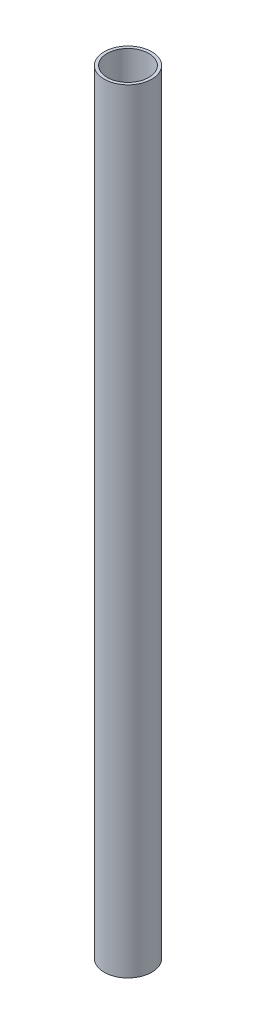
SolidWorks part; units mm, degrees
ref_plane "Front Plane" through (0, 0, 0) normal (0, 0, 1) x (1, 0, 0)
ref_plane "Top Plane" through (0, 0, 0) normal (0, 1, 0) x (1, 0, 0)
ref_plane "Right Plane" through (0, 0, 0) normal (1, 0, 0) x (0, 0, -1)
sketch "Sketch1" plane through (0, 0, 0) normal (0, 1, 0) x (1, 0, 0)
  circle A0 centre (0, 0) radius 20
  circle A1 centre (0, 0) radius 17.5
  dimension "D1" = 40
  dimension "D2" = 35
extrude "Boss-Extrude1" add sketch "Sketch1" along normal blind 650
